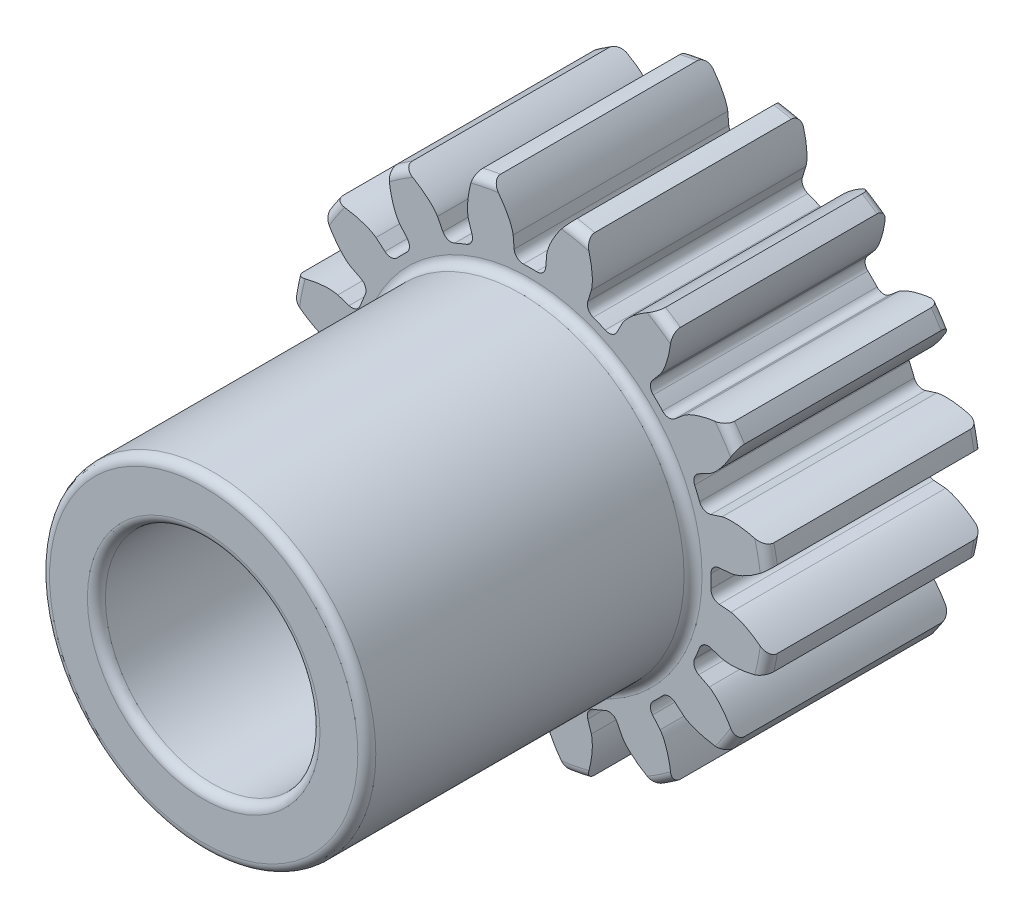
SolidWorks part; units mm, degrees
ref_plane "Front Plane" through (0, 0, 0) normal (0, 0, 1) x (1, 0, 0)
ref_plane "Top Plane" through (0, 0, 0) normal (0, 1, 0) x (1, 0, 0)
ref_plane "Right Plane" through (0, 0, 0) normal (1, 0, 0) x (0, 0, -1)
sketch "Sketch1" plane through (0, 0, 0) normal (0, 0, 1) x (1, 0, 0)
  line L0 (0, 0) -> (0, 3.175) construction
  line L1 (-1.0204, 3.5464) -> (1.0204, 2.8036) construction
  circle A0 centre (0, 0) radius 2.6789 construction
  circle A1 centre (0, 0) radius 3.5719 construction
  circle A2 centre (0, 0) radius 3.175 construction
  circle A3 centre (0, 0) radius 2.9835 construction
  circle A4 centre (0, 0) radius 1.5875 construction
  circle A5 centre (0, 0) radius 2.413 construction
  point P8 (812.8, 0)
  point P13 (203.2, 0)
  dimension "OD | Outside Diameter" = 7.1437
  dimension "Root Diameter" = 5.3578
  dimension "Gear Pitch Diameter" = 6.35
  dimension "Base Diameter" = 5.967
  dimension "For Shaft Diameter" = 3.175
  dimension "Hub Diameter" = 4.826
  dimension "Pressure Angle" = 20
  dimension "Number of Teeth" = 406.4
  dimension "Gear Pitch | Diametral Pitch" = 1625.6
sketch "Sketch2" plane through (0, 0, 0) normal (1, 0, 0) x (0, 0, -1)
  line L0 (-4.0005, 0) -> (4.0005, 0) construction
  line L1 (-4.0005, 3.5719) -> (4.0005, 3.5719) construction
  point P2 (0, 3.5719)
  point P4 (0.8255, 0)
  point P6 (0.8255, 3.5719)
  dimension "Overall Width" = 8.001
  dimension "Hub Width" = 4.826
  dimension "Face Width" = 3.175
sketch "Sketch3" plane through (0, 0, 0) normal (0, 0, 1) x (1, 0, 0)
  circle A0 centre (0, 0) radius 3.5719
  circle A1 centre (0, 0) radius 3.5719 construction
extrude "Boss-Extrude1" add sketch "Sketch3" against normal up to vertex (4.0005 mm away) and the other way up to vertex (4.0005 mm away) up to point (0, 0, -4.0005) other way up to point (0, 0, 4.0005)
sketch "Sketch5" plane through (0, 0, 0) normal (1, 0, 0) x (0, 0, -1)
  line L1 (-4.0005, 3.5719) -> (0.8255, 3.5719)
  line L2 (-4.0005, 3.5719) -> (-4.0005, 2.413)
  line L3 (-4.0005, 2.413) -> (0.8255, 2.413)
  line L4 (0.8255, 3.5719) -> (0.8255, 2.413)
  line L11 (4.0005, 1.5875) -> (-4.0005, 1.5875)
  line L12 (4.0005, 1.5875) -> (4.0005, 0)
  line L13 (4.0005, 0) -> (-4.0005, 0)
  line L14 (-4.0005, 1.5875) -> (-4.0005, 0)
  point P5 (0, 1.5875)
  point P12 (0, 2.413)
revolve "Cut-Revolve1" cut sketch "Sketch5" angle 360 about L0
fillet "Fillet2" radius 0.1332 6 edges at (3.5719, 0, -4.0005) (1.5875, 0, -4.0005) (1.5875, 0, 4.0005) (2.413, 0, -0.8255) (3.5719, 0, -0.8255) (2.413, 0, 4.0005)
sketch "Sketch4" plane through (0, 0, 0) normal (0, 0, 1) x (1, 0, 0)
  line L0 (0, 0) -> (2.6696, 0.2228) construction
  line L2 (0, 0) -> (2.6696, -0.2228) construction
  line L4 (2.6696, 0.2228) -> (2.9732, 0.2482)
  line L5 (2.9732, -0.2482) -> (2.6696, -0.2228)
  arc A0 (2.6696, 0.2228) -> (2.6696, -0.2228) centre (0, 0) cw
  arc A3 (3.5266, 0.5668) -> (3.5266, -0.5668) centre (0, 0) cw
  circle A4 centre (0, 0) radius 3.5719 construction
  spline S0 degree 4 poles (2.9732, 0.2482) (2.9741, 0.2482) (2.9768, 0.2485) (2.9818, 0.2493) (2.99, 0.2507) (3.0003, 0.2528) (3.0137, 0.256) (3.0293, 0.2602) (3.0463, 0.2654) (3.0648, 0.2716) (3.0831, 0.2782) (3.1012, 0.2853) (3.1192, 0.2927) (3.1408, 0.3022) (3.1665, 0.3143) (3.1964, 0.3293) (3.2298, 0.3476) (3.2636, 0.3673) (3.2964, 0.3877) (3.3292, 0.4095) (3.3606, 0.4313) (3.3928, 0.4551) (3.4222, 0.4776) (3.4547, 0.5041) (3.4808, 0.5258) (3.5146, 0.5558) (3.5344, 0.5739) (3.5573, 0.5955) (3.5674, 0.6053) (3.5736, 0.6113) knots 0 0 0 0 0 0.005377 0.015084 0.028532 0.04661 0.064855 0.092111 0.119476 0.146842 0.174209 0.201575 0.228941 0.256307 0.307035 0.361767 0.4165 0.471232 0.525964 0.580697 0.635429 0.690161 0.744894 0.799626 0.854358 0.909091 0.954545 1 1 1 1 1 construction
  spline S1 degree 4 poles (2.9732, 0.2482) (2.9741, 0.2482) (2.9768, 0.2485) (2.9818, 0.2493) (2.99, 0.2507) (3.0003, 0.2528) (3.0137, 0.256) (3.0293, 0.2602) (3.0463, 0.2654) (3.0648, 0.2716) (3.0831, 0.2782) (3.1012, 0.2853) (3.1192, 0.2927) (3.1408, 0.3022) (3.1665, 0.3143) (3.1964, 0.3293) (3.2298, 0.3476) (3.2636, 0.3673) (3.2964, 0.3877) (3.3292, 0.4095) (3.3606, 0.4313) (3.3928, 0.4551) (3.4222, 0.4776) (3.4547, 0.5041) (3.4808, 0.5258) (3.5073, 0.5493) (3.5201, 0.5609) (3.5266, 0.5668) knots 0 0 0 0 0 0.005377 0.015084 0.028532 0.04661 0.064855 0.092111 0.119476 0.146842 0.174209 0.201575 0.228941 0.256307 0.307035 0.361767 0.4165 0.471232 0.525964 0.580697 0.635429 0.690161 0.744894 0.799626 0.854358 0.909091 0.909091 0.909091 0.909091 0.909091
  spline S2 degree 4 poles (2.9732, -0.2482) (2.9741, -0.2482) (2.9768, -0.2485) (2.9818, -0.2493) (2.99, -0.2507) (3.0003, -0.2528) (3.0137, -0.256) (3.0293, -0.2602) (3.0463, -0.2654) (3.0648, -0.2716) (3.0831, -0.2782) (3.1012, -0.2853) (3.1192, -0.2927) (3.1408, -0.3022) (3.1665, -0.3143) (3.1964, -0.3293) (3.2298, -0.3476) (3.2636, -0.3673) (3.2964, -0.3877) (3.3292, -0.4095) (3.3606, -0.4313) (3.3928, -0.4551) (3.4222, -0.4776) (3.4547, -0.5041) (3.4808, -0.5258) (3.5146, -0.5558) (3.5344, -0.5739) (3.5573, -0.5955) (3.5674, -0.6053) (3.5736, -0.6113) knots 0 0 0 0 0 0.005377 0.015084 0.028532 0.04661 0.064855 0.092111 0.119476 0.146842 0.174209 0.201575 0.228941 0.256307 0.307035 0.361767 0.4165 0.471232 0.525964 0.580697 0.635429 0.690161 0.744894 0.799626 0.854358 0.909091 0.954545 1 1 1 1 1 construction
  spline S3 degree 4 poles (2.9732, -0.2482) (2.9741, -0.2482) (2.9768, -0.2485) (2.9818, -0.2493) (2.99, -0.2507) (3.0003, -0.2528) (3.0137, -0.256) (3.0293, -0.2602) (3.0463, -0.2654) (3.0648, -0.2716) (3.0831, -0.2782) (3.1012, -0.2853) (3.1192, -0.2927) (3.1408, -0.3022) (3.1665, -0.3143) (3.1964, -0.3293) (3.2298, -0.3476) (3.2636, -0.3673) (3.2964, -0.3877) (3.3292, -0.4095) (3.3606, -0.4313) (3.3928, -0.4551) (3.4222, -0.4776) (3.4547, -0.5041) (3.4808, -0.5258) (3.5073, -0.5493) (3.5201, -0.5609) (3.5266, -0.5668) knots 0 0 0 0 0 0.005377 0.015084 0.028532 0.04661 0.064855 0.092111 0.119476 0.146842 0.174209 0.201575 0.228941 0.256307 0.307035 0.361767 0.4165 0.471232 0.525964 0.580697 0.635429 0.690161 0.744894 0.799626 0.854358 0.909091 0.909091 0.909091 0.909091 0.909091
  dimension "D1" = 5.3578
extrude "Cut-Extrude1" cut sketch "Sketch4" against normal through all both and the other way through all
fillet "Fillet1" radius 0.1332 2 edges at (2.6696, -0.2228, -2.413) (2.6696, 0.2228, -2.413)
pattern_circular "CirPattern1" count 16 over 360 about axis through (0, 0, 4.0005) along (0, 0, -1) of "Cut-Extrude1", "Fillet1"
equation "\"Root Diameter@Sketch1\"=\"Root Diameter\""
equation "\"OD | Outside Diameter@Sketch1\"=\"Outside Diameter\""
equation "\"D1@CirPattern1\"=\"Number of Teeth\""
equation "\"Diametral Pitch\"= 64"
equation "\"Number of Teeth\"= 16"
equation "\"Pressure Angle\"=20"
equation "\"Pitch Diameter\"= \"Number of Teeth\" / \"Diametral Pitch\""
equation "\"Base Diameter\"= \"Pitch Diameter\" * cos ( \"Pressure Angle\" )"
equation "\"Outside Diameter\"= ( \"Number of Teeth\" + 2 ) / \"Diametral Pitch\""
equation "\"Dedendum\"= 1.25 / \"Diametral Pitch\""
equation "\"Root Diameter\"= \"Pitch Diameter\" - ( 2 * \"Dedendum\" )"
equation "\"Pitch Angle\"= 360deg / \"Number of Teeth\""
equation "\"Alpha\"= sqr ( \"Pitch Diameter\" ^ 2 - \"Base Diameter\" ^ 2 ) / \"Base Diameter\" * 180 / PI - \"Pressure Angle\""
equation "\"Beta\"= ( \"Pitch Angle\" / 4 - \"Alpha\" )"
equation "\"Phi\"= sqr ( ( \"Outside Diameter\" / 2 ) ^ 2 - ( \"Base Diameter\" / 2 ) ^ 2 ) / ( \"Base Diameter\" / 2 )"
equation "\"Addendum\"= 1 / \"Diametral Pitch\""
equation "\"WorkingDepth\"= 2 / \"Diametral Pitch\""
equation "\"WholeDepth\"= 2.25 / \"Diametral Pitch\""
equation "\"Clearance\"= 0.25 / \"Diametral Pitch\""
equation "\"ToothThickness\"= ( pi * 2 ) / \"Diametral Pitch\""
equation "\"CircularPitch\"= pi / \"Diametral Pitch\""
equation "\"Number of Teeth@Sketch1\"=\"Number of Teeth\""
equation "\"Gear Pitch | Diametral Pitch@Sketch1\"=\"Diametral Pitch\""
equation "\"Pressure Angle@Sketch1\"=\"Pressure Angle\""
equation "\"Gear Pitch Diameter@Sketch1\"=\"Pitch Diameter\""
equation "\"Base Diameter@Sketch1\"=\"Base Diameter\""
equation "\"Fillet\"= \"Clearance\" * cos ( \"Pressure Angle\" ) * tan ( ( 90 + \"Pressure Angle\" ) / 2 )"
equation "\"D1@Fillet1\"=\"Fillet\""
equation "\"D1@Sketch4\"=if( \"Base Diameter\">\"Root Diameter\",\"Root Diameter\",\"Base Diameter\"-.00001)"
equation "\"D1@Fillet2\"=\"Fillet\""
